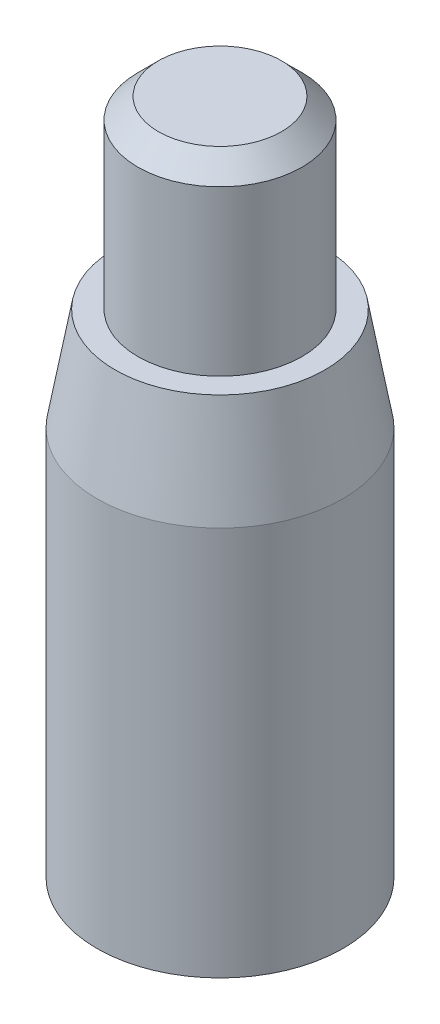
SolidWorks part; units mm, degrees
ref_plane "Plan de face" through (0, 0, 0) normal (0, 0, 1) x (1, 0, 0)
ref_plane "Plan de dessus" through (0, 0, 0) normal (0, 1, 0) x (1, 0, 0)
ref_plane "Plan de droite" through (0, 0, 0) normal (1, 0, 0) x (0, 0, -1)
sketch "Esquisse1" plane through (0, 0, 0) normal (0, 0, 1) x (1, 0, 0)
  line L0 (0, 0) -> (0, 58.9253) construction
  line L1 (0, 0) -> (6, 0)
  line L2 (6, 0) -> (6, 19)
  line L3 (4, 24) -> (5.1184, 24)
  line L4 (4, 24) -> (4, 33)
  line L5 (4, 33) -> (0, 33)
  line L6 (0, 33) -> (0, 0)
  line L7 (5.1184, 24) -> (6, 19)
  dimension "D1" = 9
  dimension "D2" = 4
  dimension "D3" = 6
  dimension "D4" = 10
  dimension "D5" = 5
  dimension "D6" = 33
revolve "Révolution1" add sketch "Esquisse1" angle 360 about L0
cosmetic thread "Représentation de filetage1" parameters "D1"=9, "D2"=7
chamfer "Chanfrein1" distance 1 angle 45 1 edges at (0, 33, -4)
